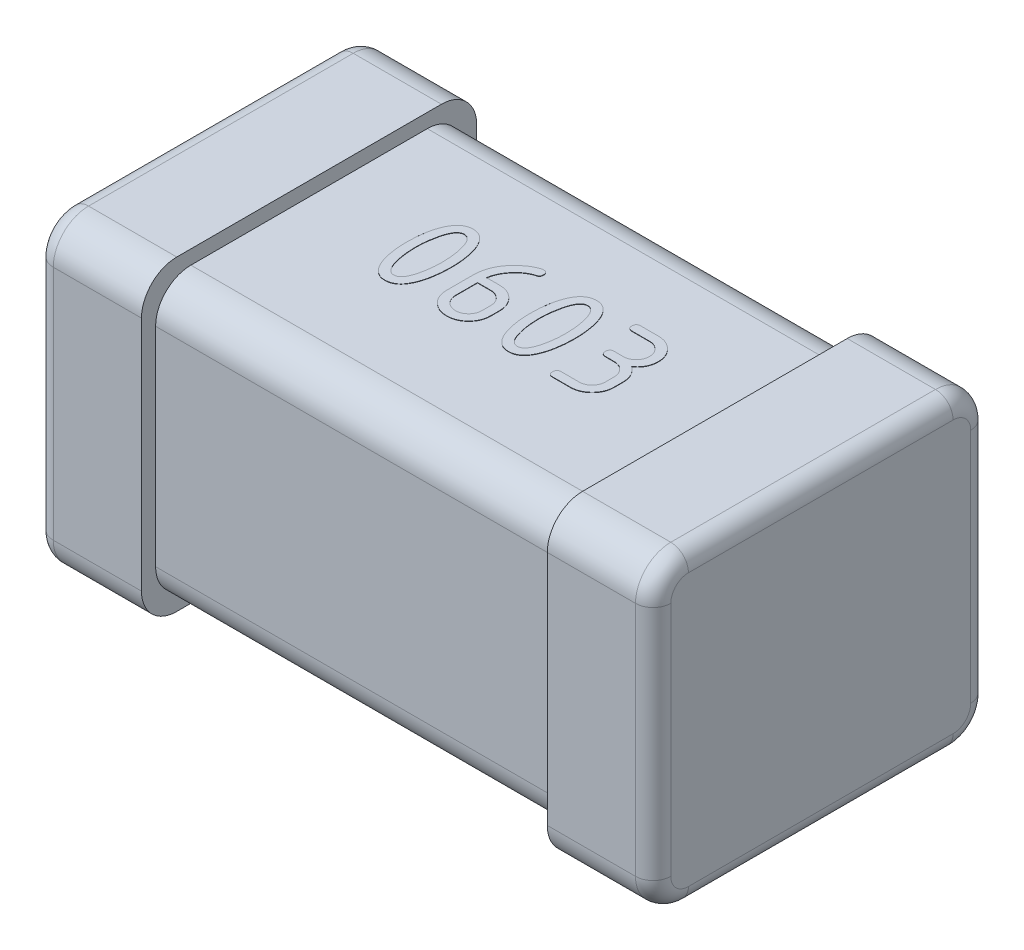
SolidWorks part; units mm, degrees
ref_plane "Front" through (0, 0, 0) normal (0, 0, 1) x (1, 0, 0)
ref_plane "Top" through (0, 0, 0) normal (0, 1, 0) x (1, 0, 0)
ref_plane "Right" through (0, 0, 0) normal (1, 0, 0) x (0, 0, -1)
sketch "Sketch1" plane through (0, 0, 0) normal (0, 1, 0) x (1, 0, 0)
  line L1 (-0.875, -0.475) -> (0.875, -0.475)
  line L2 (-0.875, -0.475) -> (-0.875, 0.475)
  line L3 (-0.875, 0.475) -> (0.875, 0.475)
  line L4 (0.875, -0.475) -> (0.875, 0.475)
  line L5 (-0.875, -0.475) -> (0.875, 0.475) construction
  line L6 (-0.875, 0.475) -> (0.875, -0.475) construction
  point P0 (0, 0)
  dimension "D1" = 0.95
  dimension "D2" = 1.75
extrude "Boss-Extrude1" add sketch "Sketch1" along normal mid plane 0.87
sketch "Sketch3" plane through (0, 0, 0) normal (1, 0, 0) x (0, 0, -1)
  line L8 (-0.435, -0.395) -> (0.435, -0.395)
  line L9 (0.435, -0.395) -> (0.435, 0.395)
  line L10 (0.435, 0.395) -> (-0.435, 0.395)
  line L11 (-0.435, 0.395) -> (-0.435, -0.395)
  line L12 (-0.435, -0.395) -> (0.435, -0.395)
  line L13 (0.435, -0.395) -> (0.435, 0.395)
  line L14 (0.435, 0.395) -> (-0.435, 0.395)
  line L15 (-0.435, 0.395) -> (-0.435, -0.395)
  dimension "D1" = 0.04
extrude "Cut-Extrude1" cut sketch "Sketch3" against normal offset from surface 0.3 and the other way offset from surface (0.575 mm away) 0.3 flip side to cut up to face at (-0.875, 0, 0) other way up to face at (0.875, 0, 0)
fillet "Fillet1" radius 0.1 4 edges at (0, -0.395, -0.435) (0, 0.395, -0.435) (0, -0.395, 0.435) (0, 0.395, 0.435)
fillet "Fillet2" radius 0.1 8 edges at (-0.725, -0.435, 0.475) (-0.725, 0.435, 0.475) (0.725, 0.435, 0.475) (0.725, -0.435, 0.475) (-0.725, -0.435, -0.475) (-0.725, 0.435, -0.475) (0.725, 0.435, -0.475) (0.725, -0.435, -0.475)
fillet "Fillet3" radius 0.05 16 edges at (0.875, 0.4057, -0.4457) (0.875, 0, -0.475) (0.875, -0.4057, -0.4457) (0.875, -0.435, 0) (0.875, -0.4057, 0.4457) (0.875, 0, 0.475) (0.875, 0.4057, 0.4457) (0.875, 0.435, 0) (-0.875, -0.4057, -0.4457) (-0.875, 0, -0.475) (-0.875, 0.4057, -0.4457) (-0.875, 0.435, 0) (-0.875, 0.4057, 0.4457) (-0.875, 0, 0.475) (-0.875, -0.4057, 0.4457) (-0.875, -0.435, 0)
sketch "Sketch4" plane through (0, 0.395, 0) normal (0, 1, 0) x (1, 0, 0)
  line L0 (-0.575, -0.0977) -> (0.575, -0.0977) construction
  line L1 (-0.575, -0.335) -> (-0.575, 0.335) construction
  line L2 (0.575, -0.375) -> (0.575, 0.375) construction
  text T0 "0603" font "ISOCPEUR" height 0.25
extrude "Boss-Extrude2" add sketch "Sketch4" along normal blind 0.001
